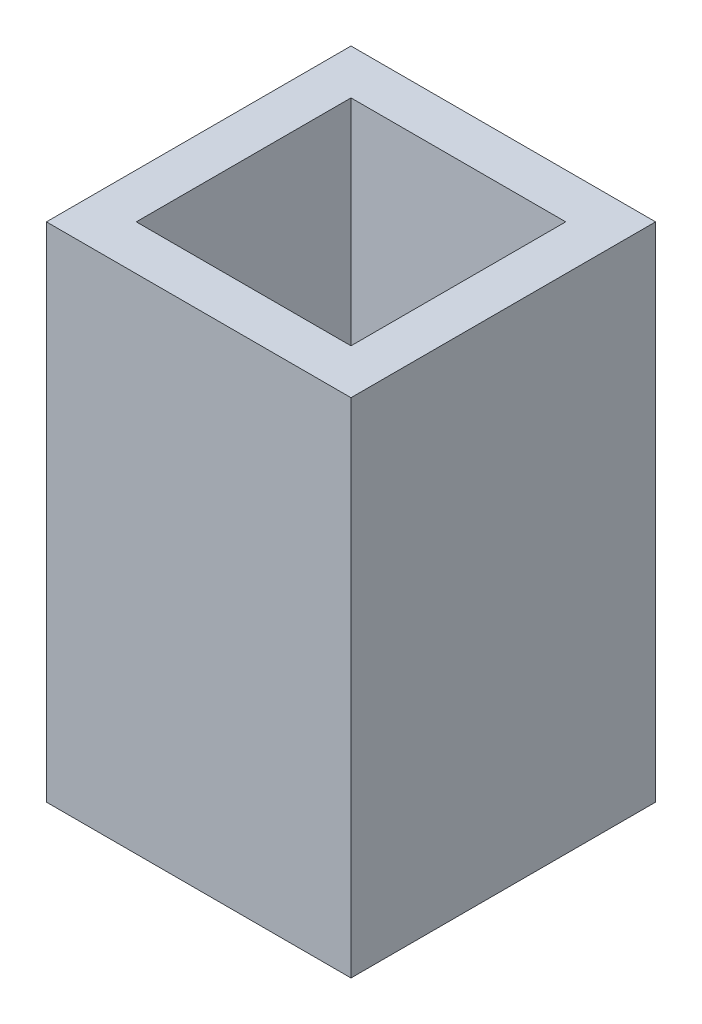
SolidWorks part; units mm, degrees
ref_plane "Front Plane" through (0, 0, 0) normal (0, 0, 1) x (1, 0, 0)
ref_plane "Top Plane" through (0, 0, 0) normal (0, 1, 0) x (1, 0, 0)
ref_plane "Right Plane" through (0, 0, 0) normal (1, 0, 0) x (0, 0, -1)
sketch "Sketch2" plane through (0, -2.5, 0) normal (0, -1, 0) x (1, 0, 0)
  line L1 (-49.75, -50) -> (-10, -50) construction
  line L2 (50, 50) -> (-50, 50)
  line L3 (50, 50) -> (50, -50)
  line L4 (50, -50) -> (-50, -50)
  line L5 (-50, 50) -> (-50, -50)
  line L6 (50, 50) -> (-50, -50) construction
  line L7 (50, -50) -> (-50, 50) construction
  line L9 (-50, -16.25) -> (-50, -36.25) construction
  point P2 (0, 0)
extrude "Boss-Extrude1" add sketch "Sketch2" along normal up to surface (165 mm away)
sketch "Sketch3" plane through (0, -2.5, 0) normal (0, 1, 0) x (1, 0, 0)
  line L0 (35, -35.25) -> (15.25, -35.25) construction
  line L1 (-35.25, -35.25) -> (35.25, -35.25)
  line L2 (-35.25, -35.25) -> (-35.25, 35.25)
  line L3 (-35.25, 35.25) -> (35.25, 35.25)
  line L4 (35.25, -35.25) -> (35.25, 35.25)
  line L5 (-35.25, -35.25) -> (35.25, 35.25) construction
  line L6 (-35.25, 35.25) -> (35.25, -35.25) construction
  line L7 (35.25, -40.25) -> (35.25, -20.25) construction
  point P0 (0, 0)
extrude "Cut-Extrude1" cut sketch "Sketch3" against normal blind 164 draft 2
